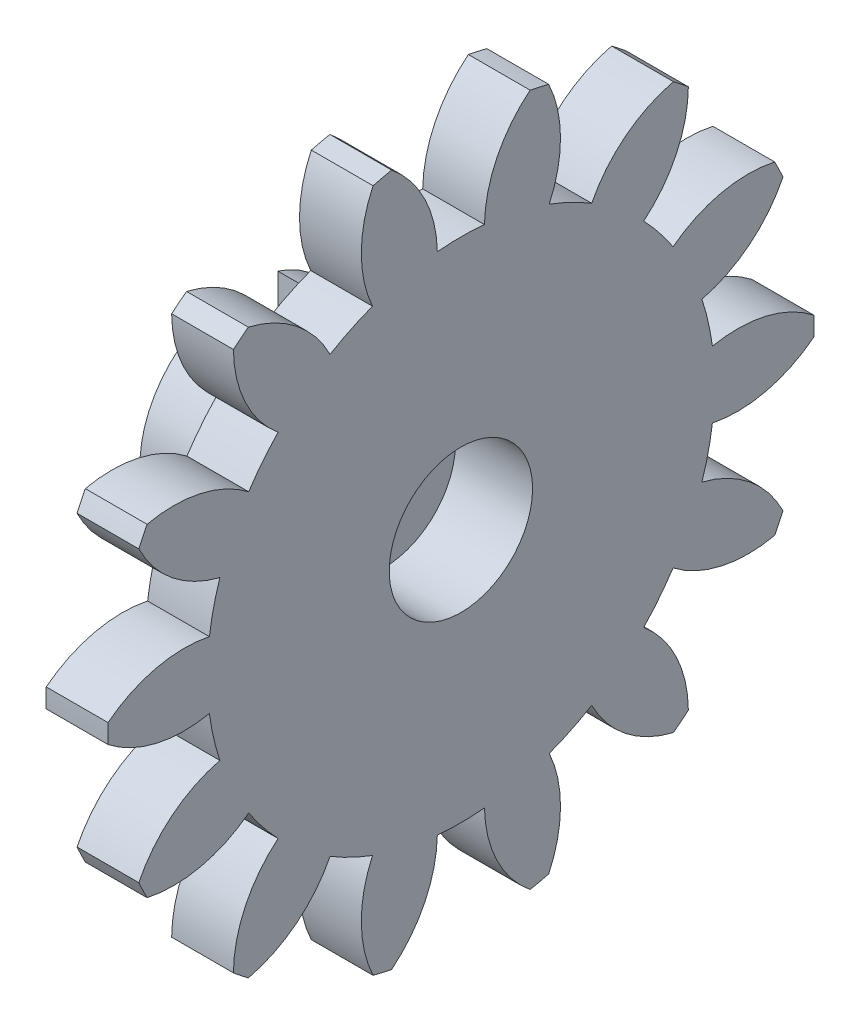
SolidWorks part; units mm, degrees
ref_plane "Plane1" through (0, 0, 0) normal (0, 0, 1) x (1, 0, 0)
ref_plane "Plane2" through (0, 0, 0) normal (0, 1, 0) x (1, 0, 0)
ref_plane "Plane3" through (0, 0, 0) normal (1, 0, 0) x (0, 0, -1)
sketch "HoldingSke" plane through (0, 0, 0) normal (0, 1, 0) x (1, 0, 0)
  line L0 (0, 0) -> (0.4851, -0.121)
  line L1 (-15, 0) -> (100, 0) construction
  line L2 (0, 0) -> (-2.1039, 2.3779)
  line L3 (0, 0) -> (-11.863, 4.5341)
  line L4 (0, 0) -> (8.3795, 2.0892)
  line L5 (0, 0) -> (-46.8476, -17.4728)
  line L6 (0, 0) -> (-2.3211, -1.5661)
  line L7 (-2.1039, 2.3779) -> (8.6586, 51.2059)
  line L8 (-76.2, 54.61) -> (-75.7, 54.61)
  line L9 (-71.009, 38.7566) -> (-53.1078, 45.2721)
  line L10 (-76.2, 71.12) -> (104.1128, 71.12)
  line L11 (0, 0) -> (-2.8, 0)
  line L12 (-76.2, 101.6) -> (-76.133, 101.6)
  line L13 (24.9733, 27.94) -> (52.9518, 28.4284)
  line L14 (24.9733, 27.94) -> (24.9743, 27.94)
  line L15 (24.9733, 27.94) -> (100.4006, 29.5858)
  line L16 (-63.627, -2) -> (-12.827, -2)
  circle A0 centre (0, 0) radius 1.5
  circle A1 centre (0, 0) radius 11.499
  circle A2 centre (0, 0) radius 37.5
  circle A3 centre (0, 0) radius 1.5
  dimension "MHD" = 22.998
  dimension "Hub_dia" = 75
  dimension "Bore" = 3
  dimension "MBD" = 3
  dimension "Num_teeth" = 14
  dimension "Pitch" = 0.5
  dimension "Overall_len" = 50
  dimension "Show_teeth" = 14
  dimension "Thickness" = 2.8
  dimension "OAL" = 50.0001
  dimension "T_dim" = 0.5
  dimension "Ap" = 20
  dimension "H" = 19.05
  dimension "Pitch_radius" = 180.3128
  dimension "Width" = 2.8
  dimension "Backlash" = 0.067
  dimension "Addendum_fac" = 1
  dimension "Dedendum_fac" = 1.25
  dimension "Clearance_fac" = 0.25
  dimension "Dedendum_add" = 0.001
  dimension "Module" = 2
sketch "BasProSke" plane through (0, 0, 0) normal (0, 1, 0) x (1, 0, 0)
  line L0 (-10, 0) -> (60, 0) construction
  line L1 (0, 0) -> (0, 16)
  line L2 (0, 0) -> (2.8, 0)
  line L3 (2.8, 0) -> (2.8, 16)
  line L4 (2.8, 16) -> (0, 16)
  dimension "Thickness" = 2.8
  dimension "Diameter" = 32
revolve "Base-Revolve" add sketch "BasProSke" angle 360 about L0
sketch "TooCutSke" plane through (0, 0, 0) normal (1, 0, 0) x (0, 0, -1)
  line L1 (0, 0) -> (0, 107) construction
  line L2 (0, 0) -> (-1.6846, 13.8983) construction
  line L3 (0, 0) -> (-6.1971, 27.1511) construction
  line L4 (-1.6846, 13.8983) -> (-3.0985, 13.5756) construction
  arc A0 (1.0679, 11.4493) -> (-1.0679, 11.4493) centre (0, 0) ccw
  arc A1 (3.1634, 15.7101) -> (-3.1634, 15.7101) centre (0, 0) ccw
  circle A2 centre (0, 0) radius 14 construction
  circle A3 centre (0, 0) radius 13.1557 construction
  arc A4 (-1.0679, 11.4493) -> (-3.1634, 15.7101) centre (-6.6668, 11.3413) ccw
  arc A5 (3.1634, 15.7101) -> (1.0679, 11.4493) centre (6.6668, 11.3413) ccw
  dimension "Root_dia" = 22.998
  dimension "Overcut_dia" = 32.0508
  dimension "Pitch_dia" = 28
  dimension "Base_dia" = 26.3114
  dimension "Flank_rad" = 5.6
  dimension "Half_ang" = 12.857
  dimension "Half_CT" = 1.4503
extrude "ToothCut" cut sketch "TooCutSke" along normal through all
fillet "Breaks" [suppressed] radius 0.04
fillet "RootFillets" [suppressed] radius 0.501
pattern_circular "TeethCuts" count 14 over 360 about axis through (0, 0, 0) along (1, 0, 0) of "ToothCut", "RootFillets", "Breaks"
sketch "HubNeaOneSke" plane through (0, 0, 0) normal (-1, 0, 0) x (0, 0, 1)
  circle A0 centre (0, 0) radius 11.499
  dimension "Diameter" = 22.998
extrude "HubNearOne" [suppressed] add sketch "HubNeaOneSke" along normal blind 47.2001
sketch "HubNeaBotSke" plane through (0, 0, 0) normal (-1, 0, 0) x (0, 0, 1)
  circle A0 centre (0, 0) radius 11.499
  dimension "Diameter" = 22.998
extrude "HubNearBoth" [suppressed] add sketch "HubNeaBotSke" along normal blind 23.6
ref_plane "FarPln" through (2.8, 0, 0) normal (1, 0, 0) x (0, 0, -1)
sketch "HubFarSke" plane through (2.8, 0, 0) normal (1, 0, 0) x (0, 0, -1)
  circle A0 centre (0, 0) radius 11.499
  dimension "Diameter" = 22.998
extrude "HubFar" [suppressed] add sketch "HubFarSke" along normal blind 23.6
sketch "BorSke" plane through (0, 0, 0) normal (1, 0, 0) x (0, 0, -1)
  circle A0 centre (0, 0) radius 1.5
  dimension "Diameter" = 3
extrude "Bore" cut sketch "BorSke" along normal mid plane 100.0001
sketch "KeySke" plane through (0, 0, 0) normal (1, 0, 0) x (0, 0, -1)
  line L0 (-0.6, 0) -> (-0.6, 2)
  line L1 (-0.6, 2) -> (0.6, 2)
  line L2 (0.6, 2) -> (0.6, 0)
  line L3 (0, 0) -> (0, 34) construction
  line L4 (-0.6, 0) -> (0.6, 0)
  dimension "Offset" = 2
  dimension "Width" = 1.2
extrude "Keyway" [suppressed] cut sketch "KeySke" along normal mid plane 100.0001
pattern_circular "Keyway2" [suppressed] count 2 every 90 about axis through (-10, 0, 0) along (1, 0, 0)
sketch "ｽｹｯﾁ2" plane through (0, 0, 0) normal (-1, 0, 0) x (0, 0, 1)
  circle A0 centre (0, 0) radius 4.75
  circle A1 centre (0, 0) radius 1.5
  dimension "D1" = 9.5
extrude "ﾎﾞｽ - 押し出し1" add sketch "ｽｹｯﾁ2" along normal blind 7
sketch "ｽｹｯﾁ3" plane through (2.8, 0, 0) normal (1, 0, 0) x (0, 0, -1)
  circle A0 centre (0, 0) radius 3.25
  dimension "D1" = 6.5
extrude "ｶｯﾄ - 押し出し1" cut sketch "ｽｹｯﾁ3" against normal blind 3.5
chamfer "面取り1" distance 1.5 angle 45 1 edges at (0, 0, -4.75)
sketch "ｽｹｯﾁ4" plane through (-7, 0, 0) normal (-1, 0, 0) x (0, 0, 1)
  line L1 (1.5, -4.75) -> (-1.5, -4.75)
  line L2 (1.5, -4.75) -> (1.5, 4.75)
  line L3 (1.5, 4.75) -> (-1.5, 4.75)
  line L4 (-1.5, -4.75) -> (-1.5, 4.75)
  line L5 (1.5, -4.75) -> (-1.5, 4.75) construction
  line L6 (1.5, 4.75) -> (-1.5, -4.75) construction
  circle A0 centre (0, 0) radius 4.75 construction
  point P0 (0, 0)
  dimension "D1" = 3
extrude "ｶｯﾄ - 押し出し2" cut sketch "ｽｹｯﾁ4" against normal blind 2
equation "' \"Module@HoldingSke\" = 6.35"
equation "' \"Num_teeth@HoldingSke\" = 12"
equation "' \"Ap@HoldingSke\" =  20"
equation "' \"Ap@HoldingSke\" = 20"
equation "' \"Width@HoldingSke\" = 0.5 * 25.4"
equation "' \"Hub_dia@HoldingSke\"= 1 * 25.4"
equation "' \"Hub_dia@HoldingSke\" = 1 * 25.4"
equation "' \"Overall_len@HoldingSke\" = 1.0 * 25.4"
equation "' \"Bore@HoldingSke\" = 0.75 * 25.4"
equation "' \"T_dim@HoldingSke\" = 0.1 * 25.4"
equation "' \"Width@KeySke\" = 0.25 * 25.4"
equation "' \"Show_teeth@HoldingSke\" = 13"
equation "' \"Backlash@HoldingSke\" = 0.009 * 25.4"
equation "' \"Addendum_fac@HoldingSke\" = 1.0"
equation "' \"Dedendum_fac@HoldingSke\" = 1.25"
equation "' \"Dedendum_add@HoldingSke\" = 0.00005 * 25.4"
equation "' \"Clearance_fac@HoldingSke\" = 0.25"
equation "\"Pitch@HoldingSke\" = 1 / \"Module@HoldingSke\""
equation "\"Overcut_dia@TooCutSke\" = (\"Num_teeth@HoldingSke\" + 2 * \"Addendum_fac@HoldingSke\") / \"Pitch@HoldingSke\" + 0.002 * 25.4"
equation "\"Pitch_dia@TooCutSke\" = \"Num_teeth@HoldingSke\" / \"Pitch@HoldingSke\""
equation "\"Base_dia@TooCutSke\" = \"Num_teeth@HoldingSke\" / \"Pitch@HoldingSke\" * cos((\"Ap@HoldingSke\"  * 3.14159265 / 180))"
equation "\"Root_dia@TooCutSke\" = (\"Num_teeth@HoldingSke\" + 2) / \"Pitch@HoldingSke\" - 2 * (\"Addendum_fac@HoldingSke\" + \"Dedendum_fac@HoldingSke\") / \"Pitch@HoldingSke\" - \"Dedendum_add@HoldingSke\" * 2"
equation "\"Half_ang@TooCutSke\" = 180 / \"Num_teeth@HoldingSke\""
equation "\"Half_CT@TooCutSke\" = \"Num_teeth@HoldingSke\" / \"Pitch@HoldingSke\" * sin((3.14159265 / 2 / \"Num_teeth@HoldingSke\")) / 2 - 7 * \"Backlash@HoldingSke\" / 4"
equation "\"Flank_rad@TooCutSke\" = \"Num_teeth@HoldingSke\" / \"Pitch@HoldingSke\" / 5"
equation "\"Radius@RootFillets\" = \"Clearance_fac@HoldingSke\" / \"Pitch@HoldingSke\" + \"Dedendum_add@HoldingSke\""
equation "\"Break_rad@Breaks\" = 0.02 / \"Pitch@HoldingSke\""
equation "\"Thickness@HoldingSke\" = \"Width@HoldingSke\""
equation "\"OAL@HoldingSke\" = \"Thickness@HoldingSke\""
equation "\"MHD@HoldingSke\" = (\"Num_teeth@HoldingSke\" + 2) / \"Pitch@HoldingSke\" - 2 * (\"Addendum_fac@HoldingSke\" + \"Dedendum_fac@HoldingSke\")  / \"Pitch@HoldingSke\" - \"Dedendum_add@HoldingSke\" * 2"
equation "\"MBD@HoldingSke\" = (\"Num_teeth@HoldingSke\" + 2) / \"Pitch@HoldingSke\" - 2 * (\"Addendum_fac@HoldingSke\" + \"Dedendum_fac@HoldingSke\")  / \"Pitch@HoldingSke\" - \"Dedendum_add@HoldingSke\" * 2 - 0.002 * 25.4"
equation "\"MHD@HoldingSke\" = ((sgn( \"MHD@HoldingSke\" - \"Hub_dia@HoldingSke\" )-1)*( \"MHD@HoldingSke\" - \"Hub_dia@HoldingSke\" ))/-2+ \"Hub_dia@HoldingSke\""
equation "\"MBD@HoldingSke\" = ((sgn( \"MBD@HoldingSke\" - \"Bore@HoldingSke\" )-1)*( \"MBD@HoldingSke\" - \"Bore@HoldingSke\" ))/-2+ \"Bore@HoldingSke\""
equation "\"OAL@HoldingSke\" = ((sgn( \"OAL@HoldingSke\" - \"Overall_len@HoldingSke\" )+1)*( \"OAL@HoldingSke\" - \"Overall_len@HoldingSke\" ))/2 + \"Overall_len@HoldingSke\" + 0.000002 * 25.4"
equation "\"Num_teeth@TeethCuts\" = int( \"Show_teeth@HoldingSke\" ) + 1"
equation "\"Num_teeth@TeethCuts\" = ((sgn( \"Num_teeth@TeethCuts\" - \"Num_teeth@HoldingSke\" )-1)*( \"Num_teeth@TeethCuts\" - \"Num_teeth@HoldingSke\" ))/-2+ \"Num_teeth@HoldingSke\""
equation "\"Num_teeth@TeethCuts\" = ((sgn( \"Num_teeth@TeethCuts\" - 2.0)+1)*( \"Num_teeth@TeethCuts\" - 2.0))/2 +2.0"
equation "\"Angle@TeethCuts\" = 360.0 / \"Num_teeth@HoldingSke\""
equation "\"Diameter@BasProSke\" = (\"Num_teeth@HoldingSke\" + 2 * \"Addendum_fac@HoldingSke\") / \"Pitch@HoldingSke\""
equation "\"Thickness@BasProSke\"  = \"Thickness@HoldingSke\""
equation "' \"Fillet_rad@BasProSke\" =  \"Thickness@HoldingSke\" * 0.05"
equation "' \"Fillet_rad@BasProSke\" = \"Thickness@HoldingSke\" * 0.05"
equation "\"MHD@HoldingSke\" = ((sgn( \"MHD@HoldingSke\" - \"Root_dia@TooCutSke\" )-1)*( \"MHD@HoldingSke\" - \"Root_dia@TooCutSke\" ))/-2+ \"Root_dia@TooCutSke\""
equation "\"Diameter@HubNeaOneSke\" = \"MHD@HoldingSke\""
equation "\"Length@HubNearOne\" = \"OAL@HoldingSke\" - \"Thickness@BasProSke\""
equation "\"Diameter@HubNeaBotSke\" = \"MHD@HoldingSke\""
equation "\"Length@HubNearBoth\" = ( \"OAL@HoldingSke\" - \"Thickness@BasProSke\" ) / 2.0"
equation "\"Thickness@FarPln\" = \"Thickness@BasProSke\""
equation "\"Diameter@HubFarSke\" = \"MHD@HoldingSke\""
equation "\"Length@HubFar\" = ( \"OAL@HoldingSke\" - \"Thickness@BasProSke\" ) / 2.0"
equation "\"Diameter@BorSke\" = \"MBD@HoldingSke\""
equation "\"D1@Bore\" = \"OAL@HoldingSke\" * 2.0"
equation "\"D1@Keyway\" = \"OAL@HoldingSke\" * 2.0"
equation "\"Offset@KeySke\" = \"T_dim@HoldingSke\" + \"MBD@HoldingSke\" / 2.0"
